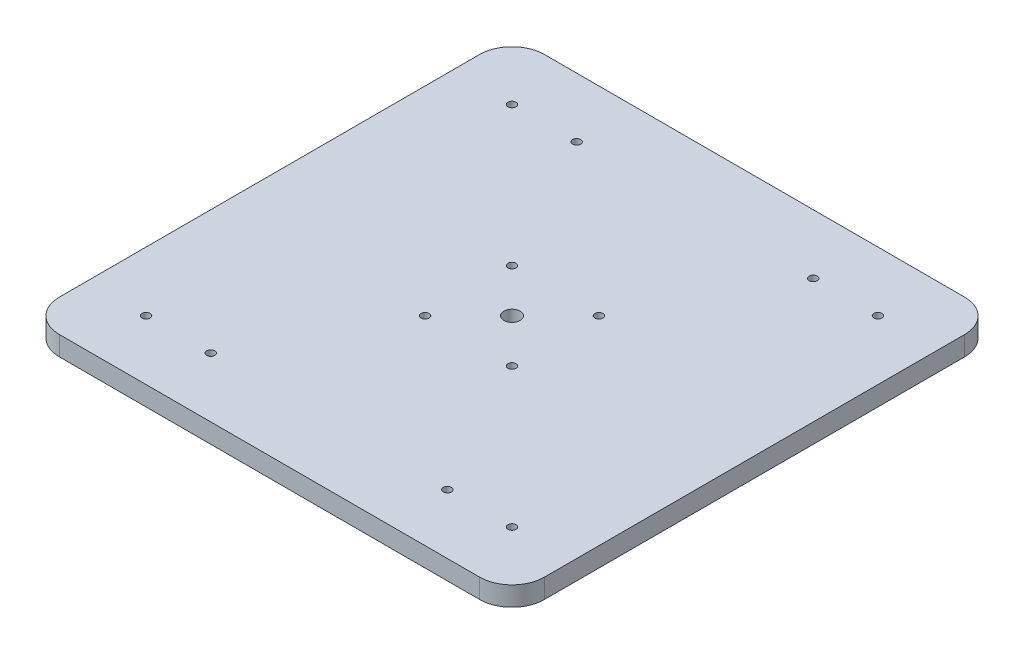
SolidWorks part; units mm, degrees
material "AISI 304"
ref_plane "前视基准面" through (0, 0, 0) normal (0, 0, 1) x (1, 0, 0)
ref_plane "上视基准面" through (0, 0, 0) normal (0, 1, 0) x (1, 0, 0)
ref_plane "右视基准面" through (0, 0, 0) normal (1, 0, 0) x (0, 0, -1)
other "Configuration Table"
sketch "草图1" plane through (0, 0, 0) normal (0, 1, 0) x (1, 0, 0)
  line L1 (-75, 75) -> (75, 75)
  line L2 (-75, 75) -> (-75, -75)
  line L3 (-75, -75) -> (75, -75)
  line L4 (75, 75) -> (75, -75)
  line L5 (-75, 75) -> (75, -75) construction
  line L6 (-75, -75) -> (75, 75) construction
  point P0 (0, 0)
  dimension "D1" = 150
  dimension "D2" = 150
extrude "凸台-拉伸1" add sketch "草图1" along normal blind 6
fillet "圆角1" radius 10 4 edges at (-75, 3, 75) (75, 3, 75) (75, 3, -75) (-75, 3, -75)
sketch "草图2" plane through (0, 6, 0) normal (0, 1, 0) x (1, 0, 0)
  line L0 (0, 0) -> (72.0711, 72.0711) construction
  arc A0 (75, 65) -> (65, 75) centre (65, 65) ccw construction
sketch "草图3" plane through (0, 0, 0) normal (0, -1, 0) x (1, 0, 0)
  line L0 (0, 0) -> (72.0711, 72.0711) construction
  arc A0 (75, 65) -> (65, 75) centre (65, 65) ccw construction
  circle A1 centre (56.5685, 56.5685) radius 1.25
  dimension "D1" = 2.5
  dimension "D2" = 80
extrude "切除-拉伸4" cut sketch "草图3" against normal through all
pattern_circular "阵列(圆周)2" count 4 over 360 about axis through (-0.0124, 0, -0.0124) along (0, 1, 0) of "切除-拉伸4"
sketch "草图7" plane through (0, 0, 0) normal (0, -1, 0) x (1, 0, 0)
  line L4 (65, 75) -> (-65, 75)
  line L5 (-75, 65) -> (-75, -65)
  line L6 (-65, -75) -> (65, -75)
  line L7 (75, -65) -> (75, 65)
  line L8 (65, 75) -> (-65, 75)
  line L9 (-75, 65) -> (-75, -65)
  line L10 (-65, -75) -> (65, -75)
  line L11 (75, -65) -> (75, 65)
  circle A0 centre (-56.5933, 56.5685) radius 1.25 construction
  circle A1 centre (-56.5933, -56.5933) radius 1.25 construction
  circle A2 centre (-56.5933, 56.5685) radius 1.25
  circle A3 centre (-56.5933, -56.5933) radius 1.25
  arc A4 (-65, 75) -> (-75, 65) centre (-65, 65) ccw
  arc A5 (-75, -65) -> (-65, -75) centre (-65, -65) ccw
  arc A6 (65, -75) -> (75, -65) centre (65, -65) ccw
  arc A7 (75, 65) -> (65, 75) centre (65, 65) ccw
  arc A8 (-65, 75) -> (-75, 65) centre (-65, 65) ccw
  arc A9 (-75, -65) -> (-65, -75) centre (-65, -65) ccw
  arc A10 (65, -75) -> (75, -65) centre (65, -65) ccw
  arc A11 (75, 65) -> (65, 75) centre (65, 65) ccw
  circle A12 centre (56.5685, 56.5685) radius 1.25 construction
  circle A13 centre (56.5685, -56.5933) radius 1.25 construction
  circle A14 centre (56.5685, 56.5685) radius 1.25
  circle A15 centre (56.5685, -56.5933) radius 1.25
  circle A16 centre (-36.5933, -56.5933) radius 1.25
  circle A17 centre (36.5685, -56.5933) radius 1.25
  circle A18 centre (-36.5933, 56.5685) radius 1.25
  circle A19 centre (36.5685, 56.5685) radius 1.25
  dimension "D1" = 0
  dimension "D2" = 2
  dimension "D3" = 2
  dimension "D4" = 2
  dimension "D5" = 2
extrude "切除-拉伸11" cut sketch "草图7" against normal blind 10 contours A18 | A19 | A16 | A17
sketch "草图9" plane through (0, 0, 0) normal (0, -1, 0) x (1, 0, 0)
  line L0 (-70.1773, 0) -> (106.2684, 0) construction
  line L1 (0, 72.4711) -> (0, -87.6775) construction
  line L2 (0, 0) -> (37.0368, 37.0368) construction
  circle A0 centre (13.435, 13.435) radius 1.25
  circle A1 centre (13.435, -13.435) radius 1.25
  circle A2 centre (-13.435, -13.435) radius 1.25
  circle A3 centre (-13.435, 13.435) radius 1.25
  point P18 (0, 0)
  dimension "D2" = 2.5
  dimension "D1" = 45
  dimension "D3" = 19
  dimension "D4" = 4
extrude "切除-拉伸12" cut sketch "草图9" against normal blind 10
sketch "草图10" plane through (0, 0, 0) normal (0, -1, 0) x (1, 0, 0)
  circle A0 centre (0, 0) radius 2.5
  dimension "D1" = 5
extrude "切除-拉伸13" cut sketch "草图10" against normal blind 10
